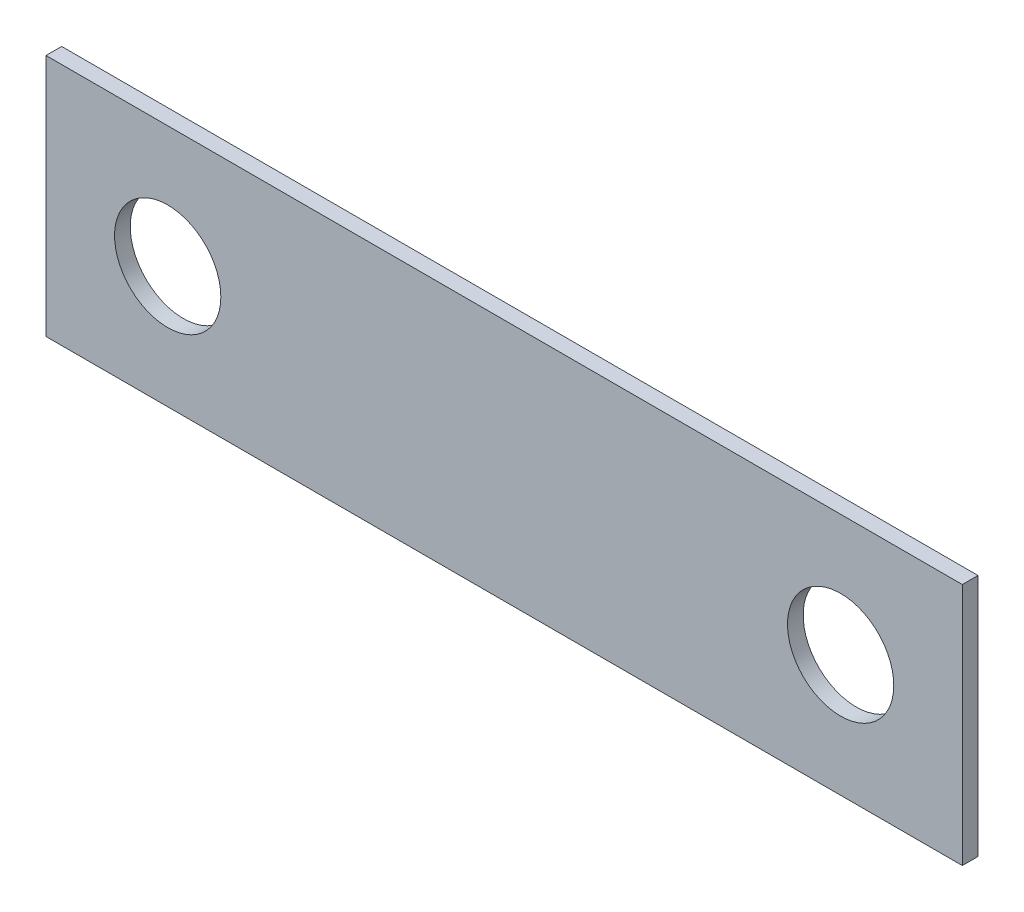
SolidWorks part; units mm, degrees
ref_plane "Front Plane" through (0, 0, 0) normal (0, 0, 1) x (1, 0, 0)
ref_plane "Top Plane" through (0, 0, 0) normal (0, 1, 0) x (1, 0, 0)
ref_plane "Right Plane" through (0, 0, 0) normal (1, 0, 0) x (0, 0, -1)
sketch "Sketch1" plane through (0, 0, 0) normal (0, 0, 1) x (1, 0, 0)
  line L1 (0, 0) -> (26.73, 0)
  line L2 (0, 0) -> (0, 7.1)
  line L3 (0, 7.1) -> (26.73, 7.1)
  line L4 (26.73, 0) -> (26.73, 7.1)
  circle A0 centre (3.55, 3.55) radius 1.55
  circle A1 centre (23.18, 3.55) radius 1.55
  point P9 (0, 3.55)
  point P10 (3.5094, 3.55)
  dimension "D4" = 3.1
  dimension "D1" = 7.1
  dimension "D2" = 26.73
  dimension "D3" = 19.63
  dimension "D5" = 3.55
extrude "Boss-Extrude1" add sketch "Sketch1" along normal blind 0.4572 contours L3 L4 L1 L2
